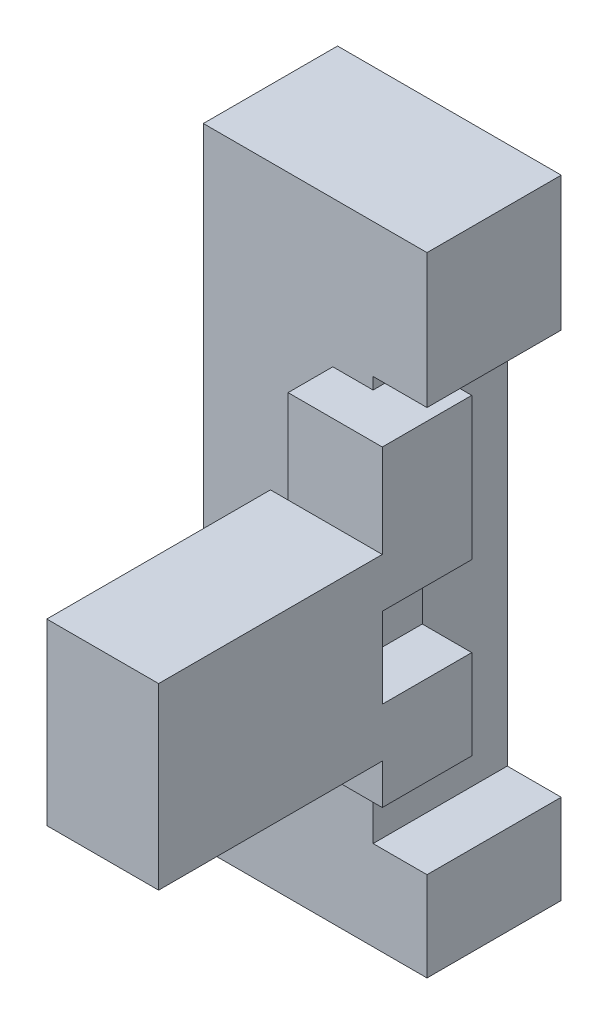
SolidWorks part; units mm, degrees
ref_plane "Alzado" through (0, 0, 0) normal (0, 0, 1) x (1, 0, 0)
ref_plane "Planta" through (0, 0, 0) normal (0, 1, 0) x (1, 0, 0)
ref_plane "Vista lateral" through (0, 0, 0) normal (1, 0, 0) x (0, 0, -1)
sketch "Croquis1" plane through (0, 0, 0) normal (0, 0, 1) x (1, 0, 0)
  line L0 (44.7148, -7.1211) -> (44.7148, -7.6211) construction
  line L1 (45.1148, -5.8211) -> (45.2206, -5.8211) construction
  line L2 (44.7148, -7.6211) -> (44.1148, -7.6211)
  line L6 (45.2206, -7.6211) -> (44.7148, -7.6211)
  line L7 (44.1148, -7.6211) -> (43.1148, -7.6211) construction
  line L8 (44.1148, -4.6411) -> (44.1148, -2.6411) construction
  line L9 (44.1148, -7.6211) -> (44.1148, -9.6211) construction
  line L10 (45.2206, -7.6211) -> (45.2206, -9.6211)
  line L11 (45.2206, -9.6211) -> (44.1148, -9.6211)
  line L12 (44.1148, -9.6211) -> (43.1148, -9.6211)
  line L13 (43.1148, -9.6211) -> (43.1148, -2.6411)
  line L14 (43.1148, -2.6411) -> (45.2206, -2.6411)
  line L15 (45.2206, -2.6411) -> (45.2206, -4.6411)
  line L16 (45.2206, -4.6411) -> (45.2206, -5.8211)
  line L17 (45.2206, -5.8211) -> (44.1148, -5.8211)
  line L18 (44.1148, -5.8211) -> (44.1148, -7.6211)
  dimension "D1" = 43.1148
  dimension "D2" = 44.1148
  dimension "D3" = 45.2206
  dimension "D4" = 2.6411
  dimension "D5" = 4.6411
  dimension "D6" = 5.8211
  dimension "D7" = 7.6211
extrude "Saliente-Extruir1" add sketch "Croquis1" along normal blind 2
sketch "Croquis2" plane through (0, 0, 2) normal (0, 0, 1) x (1, 0, 0)
  line L0 (44.1148, -6.7211) -> (44.1148, -4.7211) construction
  line L1 (44.1148, -7.6211) -> (44.1148, -5.8211) construction
  line L2 (44.1148, -6.7211) -> (44.1148, -8.7211) construction
  line L3 (45.2206, -5.8211) -> (45.2206, -2.6411) construction
  line L4 (45.2206, -4.7211) -> (42.7206, -4.7211)
  line L5 (45.2206, -4.7211) -> (45.2206, -8.7211)
  line L6 (45.2206, -8.7211) -> (42.7206, -8.7211)
  line L7 (42.7206, -4.7211) -> (42.7206, -8.7211)
  line L8 (45.2206, -7.6211) -> (44.1148, -7.6211) construction
  point P11 (42.7979, -8.7687)
  dimension "D1" = 1.3941
  dimension "D2" = 2.9
extrude "Saliente-Extruir2" add sketch "Croquis2" along normal blind 5
sketch "Croquis3" plane through (0, 0, 0) normal (0, 0, -1) x (-1, 0, 0)
  line L0 (-44.0148, -2.3777) -> (-44.0148, -9.421)
  line L5 (-44.0148, -2.3777) -> (-45.2206, -2.3777)
  line L6 (-45.2206, -2.3777) -> (-45.2206, 0.6223)
  line L7 (-45.2206, 0.6223) -> (-40.2206, 0.6223)
  line L8 (-40.2206, 0.6223) -> (-40.2206, -12.421)
  line L11 (-40.2206, -12.421) -> (-40.2206, -13.421)
  line L12 (-40.2206, -13.421) -> (-45.2206, -13.421)
  line L13 (-45.2206, -13.421) -> (-45.2206, -11.421)
  line L17 (-45.2206, -11.421) -> (-44.0148, -11.421)
  line L18 (-44.0148, -11.421) -> (-44.0148, -9.421)
  line L19 (-45.2206, -9.6211) -> (-45.2206, -7.6211) construction
  line L20 (-43.1148, -9.6211) -> (-45.2206, -9.6211) construction
  dimension "D1" = 1.2059
  dimension "D2" = 5
  dimension "D3" = 0.2001
  dimension "D4" = 7.2434
  dimension "D5" = 10.2434
  dimension "D6" = 1.7999
  dimension "D7" = 2.7999
extrude "Saliente-Extruir3" add sketch "Croquis3" along normal blind 2 and the other way blind 1
